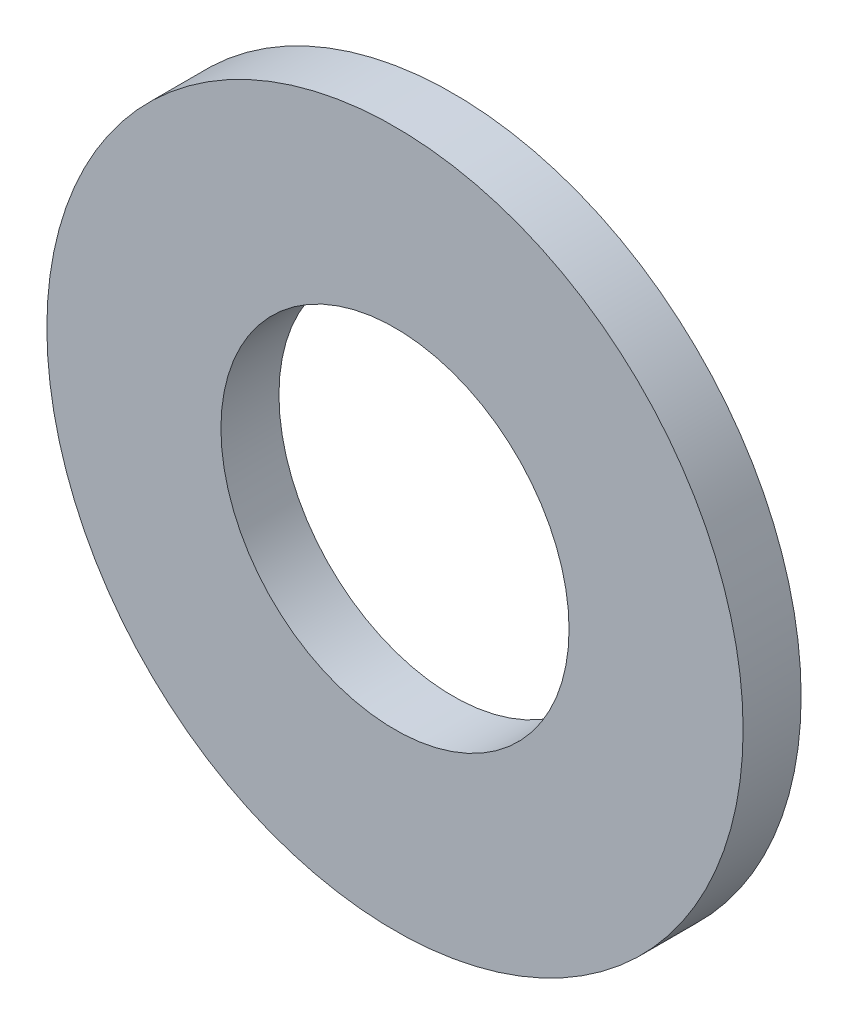
SolidWorks part; units mm, degrees
material "AISI 304"
ref_plane "Front Plane" through (0, 0, 0) normal (0, 0, 1) x (1, 0, 0)
ref_plane "Top Plane" through (0, 0, 0) normal (0, 1, 0) x (1, 0, 0)
ref_plane "Right Plane" through (0, 0, 0) normal (1, 0, 0) x (0, 0, -1)
other "Configuration Table"
sketch "Sketch1" plane through (0, 0, 0) normal (0, 0, 1) x (1, 0, 0)
  circle A0 centre (0, 0) radius 3
  circle A1 centre (0, 0) radius 1.5
  dimension "D1" = 6
  dimension "D2" = 3
extrude "Boss-Extrude1" add sketch "Sketch1" along normal blind 0.5
